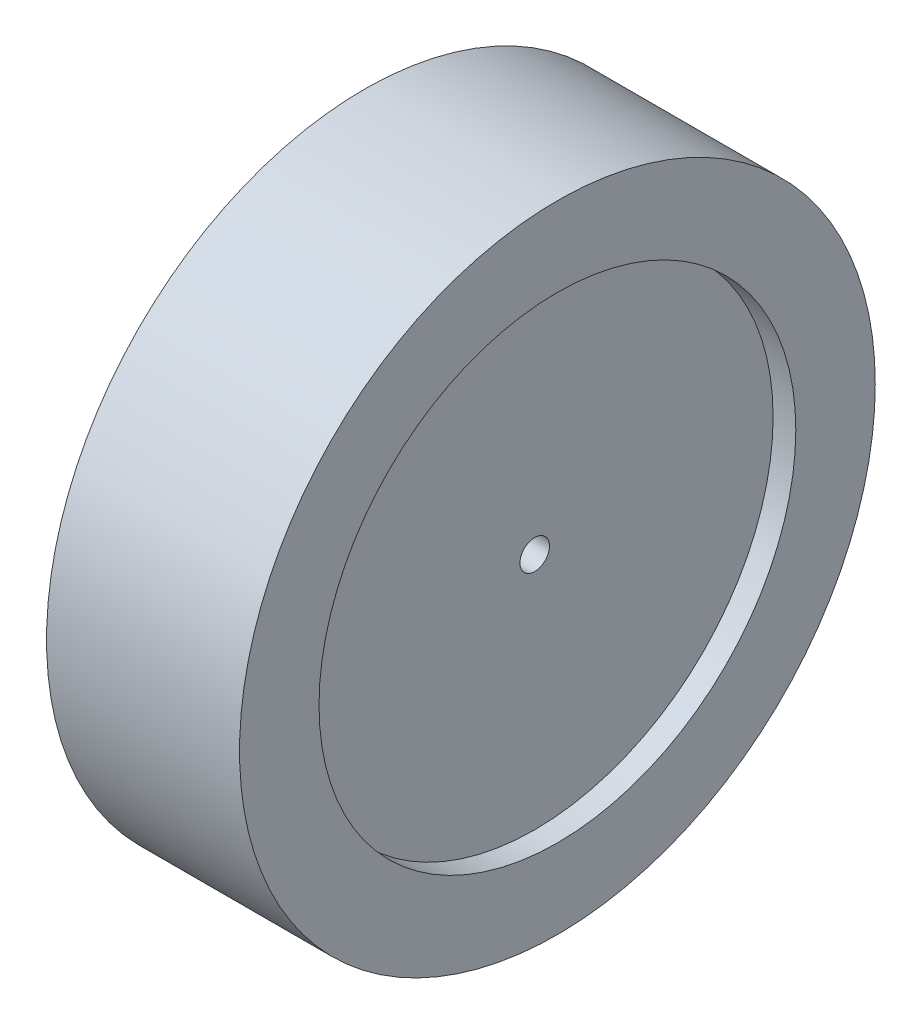
SolidWorks part; units mm, degrees
ref_plane "Plan de face" through (0, 0, 0) normal (0, 0, 1) x (1, 0, 0)
ref_plane "Plan de dessus" through (0, 0, 0) normal (0, 1, 0) x (1, 0, 0)
ref_plane "Plan de droite" through (0, 0, 0) normal (1, 0, 0) x (0, 0, -1)
sketch "Esquisse1" plane through (0, 0, 0) normal (1, 0, 0) x (0, 0, -1)
  circle A0 centre (0, 0) radius 28
  dimension "D1" = 56
extrude "Boss.-Extru.1" add sketch "Esquisse1" along normal blind 17
sketch "Esquisse2" plane through (17, 0, 0) normal (1, 0, 0) x (0, 0, -1)
  circle A0 centre (0, 0) radius 1.3
  dimension "D1" = 2.6
extrude "Enlèv. mat.-Extru.1" cut sketch "Esquisse2" against normal blind 17
sketch "Esquisse3" plane through (17, 0, 0) normal (1, 0, 0) x (0, 0, -1)
  circle A0 centre (0, 0) radius 21
  dimension "D1" = 42
extrude "Enlèv. mat.-Extru.2" cut sketch "Esquisse3" against normal blind 2
ref_plane "Plan1" through (8.5, 0, 0) normal (1, 0, 0) x (0, 0, -1)
mirror "Symétrie1" about plane through (8.5, 0, 0) normal (1, 0, 0) of "Enlèv. mat.-Extru.2"
